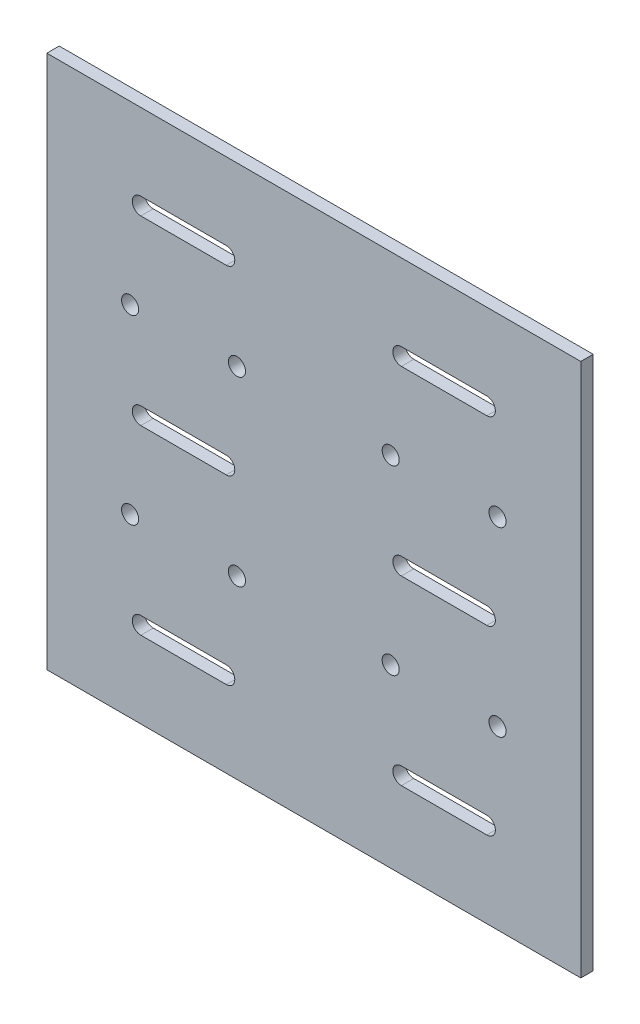
SolidWorks part; units mm, degrees
material "Бальса"
ref_plane "Спереди" through (0, 0, 0) normal (0, 0, 1) x (1, 0, 0)
ref_plane "Сверху" through (0, 0, 0) normal (0, 1, 0) x (1, 0, 0)
ref_plane "Справа" through (0, 0, 0) normal (1, 0, 0) x (0, 0, -1)
sketch "Эскиз1" plane through (0, 0, 0) normal (0, 0, 1) x (1, 0, 0)
  line L0 (125, 250) -> (125, 0) construction
  line L1 (0, 0) -> (250, 0)
  line L2 (0, 0) -> (0, 250)
  line L3 (0, 250) -> (250, 250)
  line L4 (250, 0) -> (250, 250)
  line L5 (44, 210) -> (84, 210) construction
  line L6 (44, 214) -> (84, 214)
  line L7 (44, 206) -> (84, 206)
  line L8 (166, 210) -> (206, 210) construction
  line L9 (166, 214) -> (206, 214)
  line L10 (166, 206) -> (206, 206)
  line L11 (166, 125) -> (206, 125) construction
  line L12 (166, 129) -> (206, 129)
  line L13 (166, 121) -> (206, 121)
  line L14 (166, 40) -> (206, 40) construction
  line L15 (166, 44) -> (206, 44)
  line L16 (166, 36) -> (206, 36)
  line L17 (44, 125) -> (84, 125) construction
  line L18 (44, 129) -> (84, 129)
  line L19 (44, 121) -> (84, 121)
  line L20 (44, 40) -> (84, 40) construction
  line L21 (44, 44) -> (84, 44)
  line L22 (44, 36) -> (84, 36)
  arc A0 (44, 214) -> (44, 206) centre (44, 210) ccw
  arc A1 (84, 206) -> (84, 214) centre (84, 210) ccw
  arc A2 (166, 214) -> (166, 206) centre (166, 210) ccw
  arc A3 (206, 206) -> (206, 214) centre (206, 210) ccw
  arc A4 (166, 129) -> (166, 121) centre (166, 125) ccw
  arc A5 (206, 121) -> (206, 129) centre (206, 125) ccw
  arc A6 (166, 44) -> (166, 36) centre (166, 40) ccw
  arc A7 (206, 36) -> (206, 44) centre (206, 40) ccw
  arc A8 (44, 129) -> (44, 121) centre (44, 125) ccw
  arc A9 (84, 121) -> (84, 129) centre (84, 125) ccw
  arc A10 (44, 44) -> (44, 36) centre (44, 40) ccw
  arc A11 (84, 36) -> (84, 44) centre (84, 40) ccw
  point P9 (64, 210)
  point P19 (186, 210)
  point P26 (186, 125)
  point P33 (186, 40)
  point P40 (64, 125)
  point P47 (64, 40)
  dimension "D4" = 4
  dimension "D1" = 250
  dimension "D2" = 250
  dimension "D3" = 40
  dimension "D5" = 64
  dimension "D6" = 40
  dimension "D9" = 40
  dimension "D10" = 64
  dimension "D11" = 40
  dimension "D12" = 64
  dimension "D7" = 2
  dimension "D8" = 3
extrude "Бобышка-Вытянуть1" add sketch "Эскиз1" along normal blind 5.8
sketch "Эскиз2" plane through (0, 0, 5.8) normal (0, 0, 1) x (1, 0, 0)
  line L0 (64, 206) -> (64, 129) construction
  line L1 (44, 206) -> (84, 206) construction
  line L2 (84, 129) -> (44, 129) construction
  line L3 (64, 121) -> (64, 44) construction
  line L4 (44, 121) -> (84, 121) construction
  line L5 (84, 44) -> (44, 44) construction
  line L6 (186, 206) -> (186, 44) construction
  line L7 (166, 206) -> (206, 206) construction
  line L8 (206, 44) -> (166, 44) construction
  line L9 (64, 167.5) -> (250, 167.5) construction
  line L10 (250, 0) -> (250, 250) construction
  line L11 (64, 82.5) -> (250, 82.5) construction
  line L12 (64, 167.5) -> (0, 167.5) construction
  line L13 (0, 250) -> (0, 0) construction
  line L14 (0, 167.5) -> (0, 82.5) construction
  line L15 (0, 82.5) -> (64, 82.5) construction
  line L16 (39, 167.5) -> (39, 82.5) construction
  line L17 (161, 167.5) -> (161, 82.5) construction
  line L18 (89, 167.5) -> (89, 82.5) construction
  line L20 (211, 167.5) -> (211, 82.5) construction
  circle A0 centre (39, 167.5) radius 4
  circle A1 centre (89, 167.5) radius 4
  circle A2 centre (39, 82.5) radius 4
  circle A3 centre (89, 82.5) radius 4
  circle A4 centre (161, 82.5) radius 4
  circle A5 centre (161, 167.5) radius 4
  circle A6 centre (211, 167.5) radius 4
  circle A7 centre (211, 82.5) radius 4
  dimension "D5" = 8
  dimension "D1" = 50
  dimension "D2" = 50
  dimension "D3" = 25
  dimension "D4" = 25
extrude "Вырез-Вытянуть1" cut sketch "Эскиз2" against normal up to next
